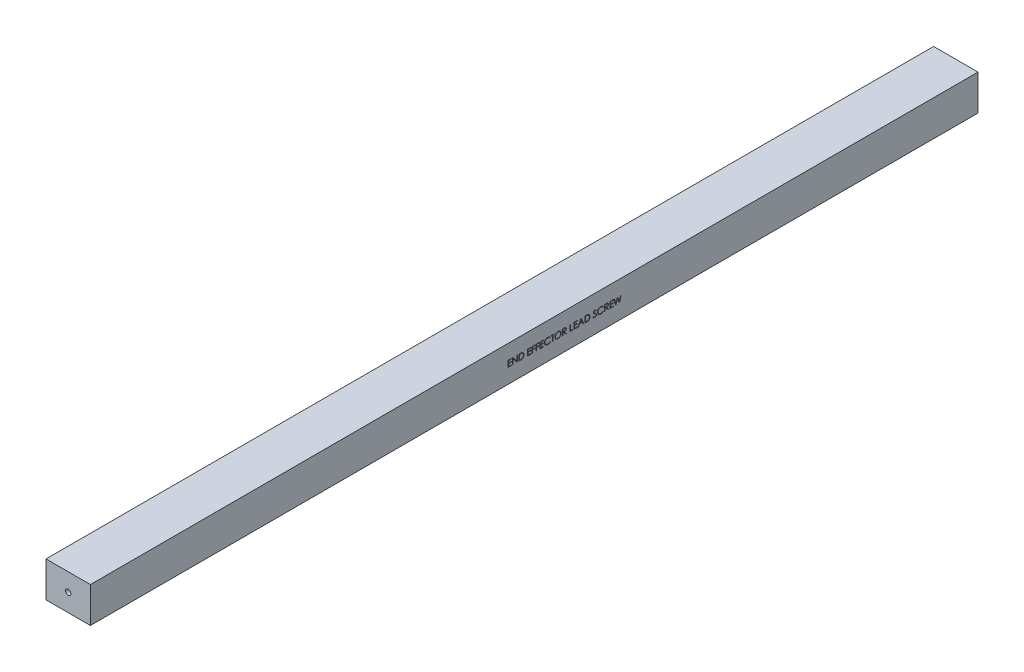
SolidWorks part; units mm, degrees
ref_plane "Front Plane" through (0, 0, 0) normal (0, 0, 1) x (1, 0, 0)
ref_plane "Top Plane" through (0, 0, 0) normal (0, 1, 0) x (1, 0, 0)
ref_plane "Right Plane" through (0, 0, 0) normal (1, 0, 0) x (0, 0, -1)
sketch "Sketch1" plane through (0, 0, 0) normal (0, 0, 1) x (1, 0, 0)
  line L1 (-12.7, 10.16) -> (12.7, 10.16)
  line L2 (-12.7, 10.16) -> (-12.7, -10.16)
  line L3 (-12.7, -10.16) -> (12.7, -10.16)
  line L4 (12.7, 10.16) -> (12.7, -10.16)
  line L5 (-12.7, 10.16) -> (12.7, -10.16) construction
  line L6 (-12.7, -10.16) -> (12.7, 10.16) construction
  point P0 (0, 0)
  dimension "D1" = 20.32
  dimension "D2" = 25.4
extrude "Boss-Extrude1" add sketch "Sketch1" along normal blind 508
sketch "Sketch2" plane through (12.7, 0, 0) normal (1, 0, 0) x (0, 0, -1)
  text T0 "END EFFECTOR LEAD SCREW\r\n"
extrude "Cut-Extrude1" cut sketch "Sketch2" against normal blind 2
sketch "Sketch3" plane through (0, 0, 508) normal (0, 0, 1) x (1, 0, 0)
  circle A0 centre (0, 0) radius 1.5
  dimension "D1" = 3
extrude "Cut-Extrude2" cut sketch "Sketch3" against normal blind 12.7
